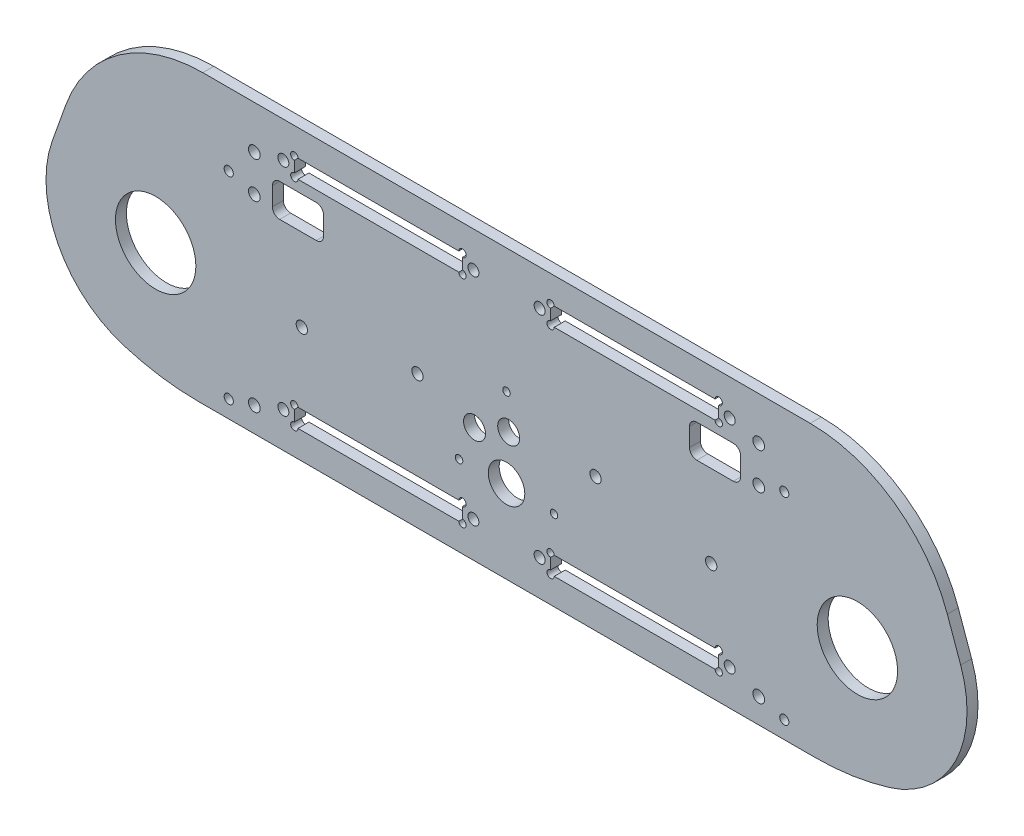
SolidWorks part; units mm, degrees
material "5052-O"
ref_plane "正面" through (0, 0, 0) normal (0, 0, 1) x (1, 0, 0)
ref_plane "平面" through (0, 0, 0) normal (0, 1, 0) x (1, 0, 0)
ref_plane "右側面" through (0, 0, 0) normal (1, 0, 0) x (0, 0, -1)
sketch "ｽｹｯﾁ1" plane through (0, 0, 0) normal (0, 0, 1) x (1, 0, 0)
  line L0 (-96, 0) -> (96, 0) construction
  line L1 (-96, 30) -> (96, 30)
  line L2 (-96, -30) -> (96, -30)
  arc A0 (-96, 30) -> (-96, -30) centre (-96, 0) ccw
  arc A1 (96, -30) -> (96, 30) centre (96, 0) ccw
  point P2 (0, 0)
  dimension "D1" = 30
  dimension "D2" = 192
extrude "ﾎﾞｽ - 押し出し1" add sketch "ｽｹｯﾁ1" along normal blind 3
sketch "ｽｹｯﾁ2" plane through (0, 0, 3) normal (0, 0, 1) x (1, 0, 0)
  line L0 (-96, 0) -> (-56, 0) construction
  line L1 (0, 30) -> (0, -30) construction
  line L2 (96, 30) -> (-96, 30) construction
  line L3 (-96, -30) -> (96, -30) construction
  line L4 (-76, 30) -> (-76, -30) construction
  line L9 (-76, 27) -> (-69, 27) construction
  line L10 (-69, 27) -> (-69, 25) construction
  line L11 (-56, 0) -> (0, 0) construction
  circle A3 centre (-96, 0) radius 24 construction
  circle A7 centre (-24.3623, 4.8014) radius 1.55
  circle A8 centre (-56, 0) radius 1.55
  circle A9 centre (-96, 0) radius 11
  circle A14 centre (24.3623, 4.8014) radius 1.55
  circle A15 centre (56, 0) radius 1.55
  circle A16 centre (96, 0) radius 11
  circle A17 centre (-76, 27) radius 1.25
  circle A18 centre (-76, -27) radius 1.25
  circle A19 centre (76, 27) radius 1.25
  circle A20 centre (76, -27) radius 1.25
  circle A24 centre (0, -9) radius 7.5 construction
  circle A26 centre (-24.3623, 4.8014) radius 16 construction
  circle A34 centre (0, -9) radius 12 construction
  circle A35 centre (-56, 0) radius 16 construction
  circle A39 centre (0, -9) radius 5
  circle A42 centre (-69, 25) radius 1.6
  circle A43 centre (-69, -25) radius 1.6
  circle A44 centre (69, -25) radius 1.6
  circle A45 centre (69, 25) radius 1.6
  point P23 (0, -2)
  point P34 (0, -2)
  point P35 (0, -9)
  dimension "D1" = 48
  dimension "D2" = 32
  dimension "D3" = 7
  dimension "D4" = 15
  dimension "D5" = 7
  dimension "D6" = 22
  dimension "D7" = 2
  dimension "D10" = 3.1
  dimension "D11" = 2.5
  dimension "D12" = 3
  dimension "D13" = 3
  dimension "D8" = 21
  dimension "D15" = 24
  dimension "D16" = 10
  dimension "D9" = 3.2
  dimension "D14" = 20
extrude "ｶｯﾄ - 押し出し1" cut sketch "ｽｹｯﾁ2" against normal through all
sketch "ｽｹｯﾁ4" plane through (0, 0, 3) normal (0, 0, 1) x (1, 0, 0)
  line L0 (-124.2607, 10.0665) -> (-120.6113, 20.3117)
  line L1 (-83.1, 46.77) -> (83.1, 46.77)
  line L2 (120.6113, 20.3117) -> (124.2607, 10.0665)
  line L3 (-96, 30) -> (96, 30)
  line L4 (-84.298, -31.75) -> (84.298, -31.75)
  line L5 (96, -30) -> (-96, -30)
  line L6 (96, 30) -> (-96, 30) construction
  arc A0 (-120.6113, 20.3117) -> (-83.1, 46.77) centre (-83.1, 6.95) cw
  arc A1 (83.1, 46.77) -> (120.6113, 20.3117) centre (83.1, 6.95) cw
  arc A2 (-124.2607, 10.0665) -> (-96, 30) centre (-96, 0) cw
  arc A3 (124.2607, 10.0665) -> (96, 30) centre (96, 0) ccw
  arc A4 (-84.298, -31.75) -> (-104.7765, -28.6875) centre (-84.298, 38.25) cw
  arc A5 (-104.7765, -28.6875) -> (-96, -30) centre (-96, 0) ccw
  arc A6 (84.298, -31.75) -> (104.7765, -28.6875) centre (84.298, 38.25) ccw
  arc A7 (104.7765, -28.6875) -> (96, -30) centre (96, 0) cw
  arc A8 (-96, 30) -> (-96, -30) centre (-96, 0) ccw construction
  arc A9 (96, -30) -> (96, 30) centre (96, 0) ccw construction
  dimension "D1" = 39.82
  dimension "D3" = 70
  dimension "D2" = 166.2
  dimension "D4" = 31.75
  dimension "D5" = 46.77
extrude "ﾎﾞｽ - 押し出し2" add sketch "ｽｹｯﾁ4" against normal up to surface (3 mm away) up to face at (54.45, 0, 0)
sketch "ｽｹｯﾁ3" plane through (0, 0, 3) normal (0, 0, 1) x (1, 0, 0)
  line L0 (0, 46.77) -> (0, -31.75) construction
  line L1 (-12.0573, 34.52) -> (-58.0573, 34.52)
  line L2 (-12.0573, 34.52) -> (-12.0573, 39.52)
  line L3 (-12.0573, 39.52) -> (-58.0573, 39.52)
  line L4 (-58.0573, 34.52) -> (-58.0573, 39.52)
  line L5 (-12.0573, 34.52) -> (-58.0573, 39.52) construction
  line L6 (-12.0573, 39.52) -> (-58.0573, 34.52) construction
  line L7 (-69, 25) -> (-69, 35) construction
  line L9 (-35.0573, 39.52) -> (-35.0573, 34.52) construction
  line L10 (-58.0573, 37.02) -> (-61.0573, 37.02) construction
  line L11 (58.0573, 37.02) -> (61.0573, 37.02) construction
  line L12 (35.0573, 39.52) -> (35.0573, 34.52) construction
  line L13 (12.0573, 39.52) -> (58.0573, 34.52) construction
  line L14 (12.0573, 34.52) -> (58.0573, 39.52) construction
  line L15 (58.0573, 34.52) -> (58.0573, 39.52)
  line L16 (12.0573, 39.52) -> (58.0573, 39.52)
  line L17 (12.0573, 34.52) -> (12.0573, 39.52)
  line L18 (12.0573, 34.52) -> (58.0573, 34.52)
  line L19 (-125.0448, 7.51) -> (125.0448, 7.51) construction
  line L20 (12.0573, -19.5) -> (58.0573, -24.5) construction
  line L21 (12.0573, -24.5) -> (58.0573, -19.5) construction
  line L22 (35.0573, -24.5) -> (35.0573, -19.5) construction
  line L23 (58.0573, -22) -> (61.0573, -22) construction
  line L24 (-58.0573, -22) -> (-61.0573, -22) construction
  line L25 (-35.0573, -24.5) -> (-35.0573, -19.5) construction
  line L26 (-12.0573, -24.5) -> (-58.0573, -19.5) construction
  line L27 (-12.0573, -19.5) -> (-58.0573, -24.5) construction
  line L28 (12.0573, -19.5) -> (58.0573, -19.5)
  line L29 (12.0573, -19.5) -> (12.0573, -24.5)
  line L30 (12.0573, -24.5) -> (58.0573, -24.5)
  line L31 (58.0573, -19.5) -> (58.0573, -24.5)
  line L32 (-58.0573, -19.5) -> (-58.0573, -24.5)
  line L33 (-12.0573, -24.5) -> (-58.0573, -24.5)
  line L34 (-12.0573, -19.5) -> (-12.0573, -24.5)
  line L35 (-12.0573, -19.5) -> (-58.0573, -19.5)
  line L36 (83.1, 46.77) -> (-83.1, 46.77) construction
  line L37 (-84.298, -31.75) -> (84.298, -31.75) construction
  circle A0 centre (-61.0573, 37.02) radius 1.5
  circle A1 centre (-9.0573, 37.02) radius 1.5
  circle A2 centre (9.0573, 37.02) radius 1.5
  circle A3 centre (61.0573, 37.02) radius 1.5
  arc A4 (-124.2607, 10.0665) -> (-104.7765, -28.6875) centre (-96, 0) ccw construction
  circle A5 centre (-69, 35) radius 1.6
  circle A6 centre (61.0573, -22) radius 1.5
  circle A7 centre (9.0573, -22) radius 1.5
  circle A8 centre (-9.0573, -22) radius 1.5
  circle A9 centre (-61.0573, -22) radius 1.5
  arc A10 (104.7765, -28.6875) -> (124.2607, 10.0665) centre (96, 0) ccw construction
  circle A11 centre (-69, 25) radius 1.6 construction
  circle A12 centre (69, 35) radius 1.6
  point P0 (-35.0573, 37.02)
  point P29 (35.0573, 37.02)
  point P60 (35.0573, -22)
  point P61 (-35.0573, -22)
  dimension "D6" = 3
  dimension "D3" = 18.1146
  dimension "D4" = 9.75
  dimension "D7" = 9.75
  dimension "D1" = 5
  dimension "D2" = 46
  dimension "D5" = 3
  dimension "D8" = 10
extrude "ｶｯﾄ - 押し出し2" cut sketch "ｽｹｯﾁ3" against normal through all
sketch "ｽｹｯﾁ5" plane through (0, 0, 3) normal (0, 0, 1) x (1, 0, 0)
  line L0 (-9.0573, 37.02) -> (-9.0573, -22) construction
  line L1 (-9.0573, -22) -> (9.0573, -22) construction
  line L2 (9.0573, -22) -> (9.0573, 37.02) construction
  line L3 (9.0573, 37.02) -> (-9.0573, 37.02) construction
  line L4 (0, 37.02) -> (0, -22) construction
  line L6 (9.0573, 7.51) -> (-9.0573, 7.51) construction
  circle A0 centre (-58.0573, 39.52) radius 1
  circle A1 centre (-58.0573, 34.52) radius 1
  circle A2 centre (-12.0573, 39.52) radius 1
  circle A3 centre (-12.0573, 34.52) radius 1
  circle A4 centre (-12.0573, -19.5) radius 1
  circle A5 centre (-12.0573, -24.5) radius 1
  circle A6 centre (-58.0573, -19.5) radius 1
  circle A7 centre (-58.0573, -24.5) radius 1
  circle A8 centre (58.0573, -24.5) radius 1
  circle A9 centre (58.0573, -19.5) radius 1
  circle A10 centre (12.0573, -24.5) radius 1
  circle A11 centre (12.0573, -19.5) radius 1
  circle A12 centre (12.0573, 34.52) radius 1
  circle A13 centre (12.0573, 39.52) radius 1
  circle A14 centre (58.0573, 34.52) radius 1
  circle A15 centre (58.0573, 39.52) radius 1
  dimension "D1" = 2
extrude "ｶｯﾄ - 押し出し3" cut sketch "ｽｹｯﾁ5" against normal through all
sketch "ｽｹｯﾁ6" plane through (0, 0, 3) normal (0, 0, 1) x (1, 0, 0)
  line L0 (0, -2.25) -> (0, -9) construction
  line L1 (-8.75, -0.1433) -> (0, -2.25) construction
  line L2 (-6.9282, -6.25) -> (6.9282, 1.75) construction
  line L3 (-8.75, -0.1433) -> (0.5875, 3.4361) construction
  line L4 (-4.0813, 1.6464) -> (-7.1596, 9.6766) construction
  line L5 (0, -2.25) -> (-12.9904, -9.75) construction
  line L6 (0, -2.25) -> (0, 12.75) construction
  line L7 (0, -2.25) -> (12.9904, -9.75) construction
  circle A0 centre (-8.75, -0.1433) radius 3
  circle A1 centre (0, -2.25) radius 3.25 construction
  circle A2 centre (0, -9) radius 5 construction
  circle A3 centre (0.5875, 3.4361) radius 3
  circle A4 centre (-6.9282, -6.25) radius 2.6 construction
  circle A5 centre (6.9282, 1.75) radius 2.6 construction
  circle A6 centre (0, -2.25) radius 17.5 construction
  circle A7 centre (0.5875, 3.4361) radius 6.675 construction
  circle A8 centre (-8.75, -0.1433) radius 6.675 construction
  circle A9 centre (0, -9) radius 10.5 construction
  circle A14 centre (0, -9) radius 3.5 construction
  circle A16 centre (-12.9904, -9.75) radius 2.1 construction
  circle A17 centre (-12.9904, -9.75) radius 1.025
  circle A18 centre (0, 12.75) radius 1.025
  circle A19 centre (0, 12.75) radius 2.1 construction
  circle A20 centre (12.9904, -9.75) radius 1.025
  circle A21 centre (12.9904, -9.75) radius 2.1 construction
  circle A22 centre (0.5875, 3.4361) radius 3.5 construction
  circle A23 centre (-8.75, -0.1433) radius 3.5 construction
  point P16 (0, -2.25)
  point P29 (0, -2.25)
  point P35 (0, -2.25)
  dimension "D1" = 12.45
  dimension "D2" = 12.45
  dimension "D3" = 10
  dimension "D4" = 6
  dimension "D5" = 6.5
  dimension "D6" = 9
  dimension "D7" = 16
  dimension "D8" = 5.2
  dimension "D10" = 35
  dimension "D11" = 13.35
  dimension "D12" = 21
  dimension "D13" = 4.2
  dimension "D9" = 7
  dimension "D15" = 2.05
  dimension "D20" = 7
  dimension "D14" = 8.6
  dimension "D17" = 15
  dimension "D18" = 60
  dimension "D19" = 60
  dimension "D16" = 3
extrude "ｶｯﾄ - 押し出し4" cut sketch "ｽｹｯﾁ6" against normal through all
sketch "ｽｹｯﾁ7" plane through (0, 0, 3) normal (0, 0, 1) x (1, 0, 0)
  line L1 (-50.0573, 22.52) -> (-64.0573, 22.52)
  line L2 (-50.0573, 22.52) -> (-50.0573, 31.52)
  line L3 (-50.0573, 31.52) -> (-64.0573, 31.52)
  line L4 (-64.0573, 22.52) -> (-64.0573, 31.52)
  line L5 (-50.0573, 22.52) -> (-64.0573, 31.52) construction
  line L6 (-50.0573, 31.52) -> (-64.0573, 22.52) construction
  line L7 (0, 0) -> (0, 46.77) construction
  line L8 (83.1, 46.77) -> (-83.1, 46.77) construction
  line L9 (50.0573, 31.52) -> (64.0573, 31.52)
  line L20 (64.0573, 22.52) -> (64.0573, 31.52)
  line L21 (50.0573, 22.52) -> (64.0573, 22.52)
  line L22 (50.0573, 22.52) -> (50.0573, 31.52)
  line L23 (-57.0573, 34.52) -> (-13.0573, 34.52) construction
  circle A0 centre (-61.0573, 37.02) radius 1.5 construction
  point P0 (-57.0573, 27.02)
  dimension "D1" = 3
  dimension "D2" = 9
  dimension "D3" = 14
  dimension "D5" = 3
extrude "ｶｯﾄ - 押し出し5" cut sketch "ｽｹｯﾁ7" against normal through all
fillet "ﾌｨﾚｯﾄ1" radius 2 8 edges at (64.0573, 31.52, 1.5) (64.0573, 22.52, 1.5) (50.0573, 31.52, 1.5) (50.0573, 22.52, 1.5) (-50.0573, 31.52, 1.5) (-50.0573, 22.52, 1.5) (-64.0573, 31.52, 1.5) (-64.0573, 22.52, 1.5)
